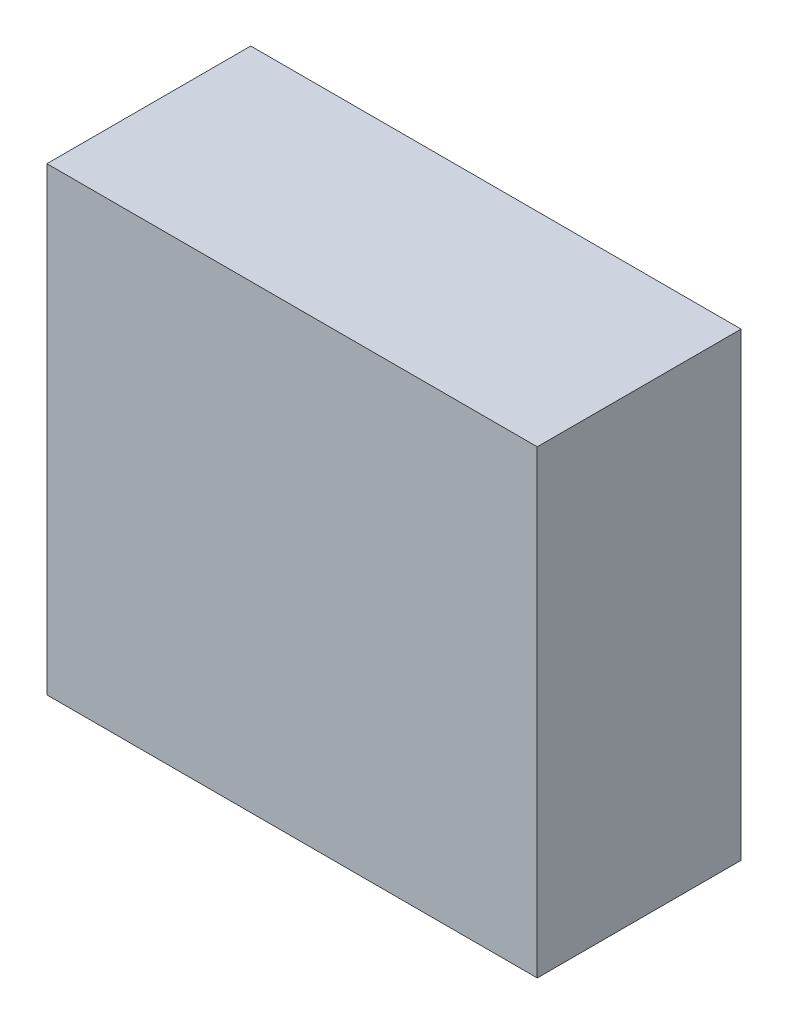
SolidWorks part; units mm, degrees
ref_plane "Front Plane" through (0, 0, 0) normal (0, 0, 1) x (1, 0, 0)
ref_plane "Top Plane" through (0, 0, 0) normal (0, 1, 0) x (1, 0, 0)
ref_plane "Right Plane" through (0, 0, 0) normal (1, 0, 0) x (0, 0, -1)
sketch "Sketch1" plane through (0, 0, 0) normal (0, 0, 1) x (1, 0, 0)
  line L1 (0, 0) -> (178, 0)
  line L2 (0, 0) -> (0, 167)
  line L3 (0, 167) -> (178, 167)
  line L4 (178, 0) -> (178, 167)
  dimension "D1" = 167
  dimension "D2" = 178
extrude "Boss-Extrude1" add sketch "Sketch1" along normal blind 74
